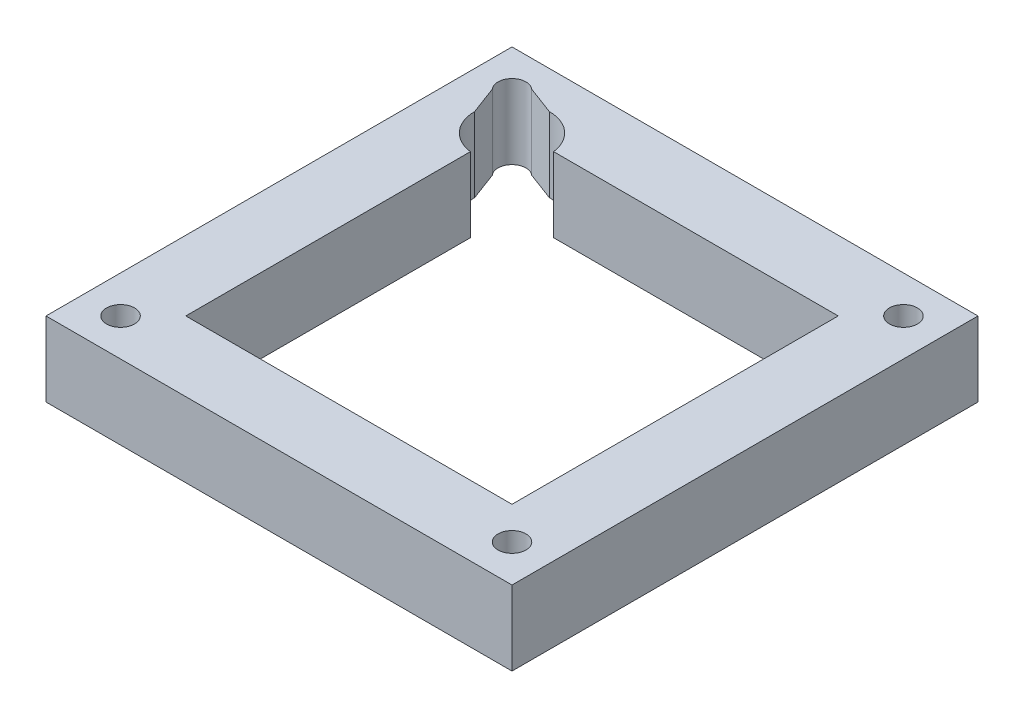
SolidWorks part; units mm, degrees
ref_plane "Front Plane" through (0, 0, 0) normal (0, 0, 1) x (1, 0, 0)
ref_plane "Top Plane" through (0, 0, 0) normal (0, 1, 0) x (1, 0, 0)
ref_plane "Right Plane" through (0, 0, 0) normal (1, 0, 0) x (0, 0, -1)
sketch "Sketch1" plane through (0, 0, 0) normal (0, 1, 0) x (1, 0, 0)
  line L0 (17.5, 17.5) -> (-13.0314, 17.5)
  line L1 (-25, -25) -> (25, -25)
  line L2 (-25, -25) -> (-25, 25)
  line L3 (-25, 25) -> (25, 25)
  line L4 (25, -25) -> (25, 25)
  line L5 (0, 25) -> (0, -25) construction
  line L6 (-25, 0) -> (25, 0) construction
  line L11 (0, 20) -> (0, -20) construction
  line L12 (-20, 0) -> (20, 0) construction
  line L13 (-17.5, -17.5) -> (17.5, -17.5)
  line L16 (17.5, -17.5) -> (17.5, 17.5)
  line L17 (0, 17.5) -> (0, -17.5) construction
  line L18 (-17.5, 0) -> (17.5, 0) construction
  line L19 (-17.5, -17.5) -> (-17.5, 13.0314)
  line L20 (-22.1301, 20.0137) -> (-21, 17)
  line L21 (-20.0137, 22.1301) -> (-17, 21)
  arc A0 (-20.0137, 22.1301) -> (-22.1301, 20.0137) centre (-21, 21) ccw
  circle A1 centre (21, 21) radius 1.5
  circle A2 centre (21, -21) radius 1.5
  circle A3 centre (-21, -21) radius 1.5
  arc A4 (-21, 17) -> (-17, 21) centre (-17, 17) ccw
  point P0 (0, 0)
  point P4 (0, 0)
  point P13 (0, 0)
  dimension "D1" = 50
  dimension "D2" = 50
  dimension "D4" = 35
extrude "Support" add sketch "Sketch1" along normal blind 8 contours L1 L4 L3 L2 A4 L0 L16 L13 L19 L20 A0 L21 A1 A2 A3
sketch "Sketch2" plane through (0, 0, 0) normal (0, 0, 1) x (1, 0, 0)
  line L4 (-10, 1.5) -> (10, 1.5)
  line L5 (-10, 1.5) -> (-10, 6.5)
  line L6 (-10, 6.5) -> (10, 6.5)
  line L7 (10, 1.5) -> (10, 6.5)
  line L8 (0, 6.5) -> (0, 1.5) construction
  line L9 (-10, 4) -> (10, 4) construction
  point P6 (0, 4)
  dimension "D1" = 20
  dimension "D2" = 5
sketch "Sketch3" plane through (0, 0, 0) normal (1, 0, 0) x (0, 0, -1)
  line L4 (-10, 1.5) -> (10, 1.5)
  line L5 (-10, 1.5) -> (-10, 6.5)
  line L6 (-10, 6.5) -> (10, 6.5)
  line L7 (10, 1.5) -> (10, 6.5)
  line L8 (0, 6.5) -> (0, 1.5) construction
  line L9 (-10, 4) -> (10, 4) construction
  point P6 (0, 4)
  dimension "D1" = 20
  dimension "D2" = 5
